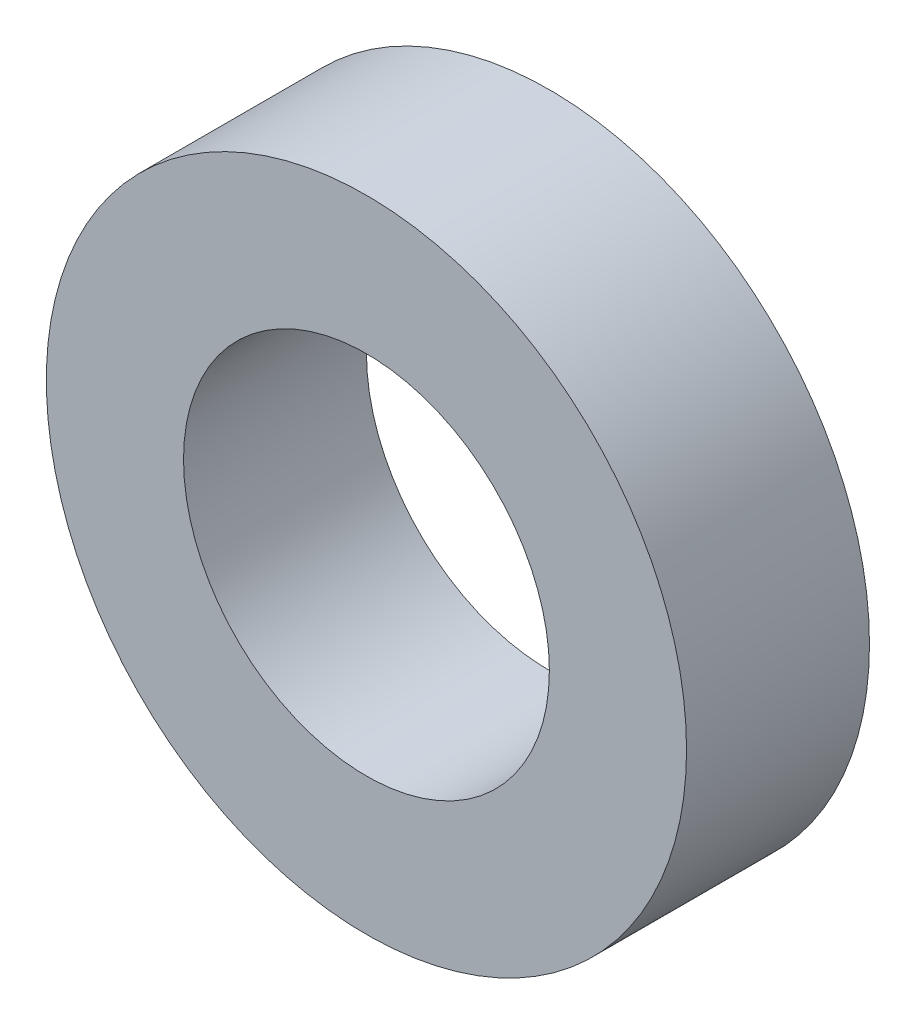
SolidWorks part; units mm, degrees
ref_plane "前视基准面" through (0, 0, 0) normal (0, 0, 1) x (1, 0, 0)
ref_plane "上视基准面" through (0, 0, 0) normal (0, 1, 0) x (1, 0, 0)
ref_plane "右视基准面" through (0, 0, 0) normal (1, 0, 0) x (0, 0, -1)
sketch "草图1" plane through (0, 0, 0) normal (0, 0, 1) x (1, 0, 0)
  circle A0 centre (0, 0) radius 4
  circle A1 centre (0, 0) radius 7
  dimension "D1" = 8
  dimension "D2" = 14
extrude "凸台-拉伸1" add sketch "草图1" along normal blind 4
